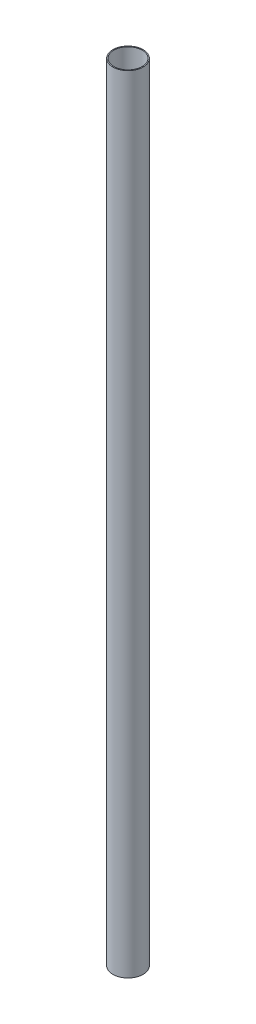
SolidWorks part; units mm, degrees
ref_plane "Front Plane" through (0, 0, 0) normal (0, 0, 1) x (1, 0, 0)
ref_plane "Top Plane" through (0, 0, 0) normal (0, 1, 0) x (1, 0, 0)
ref_plane "Right Plane" through (0, 0, 0) normal (1, 0, 0) x (0, 0, -1)
sketch "Sketch1" plane through (0, 0, 0) normal (0, 1, 0) x (1, 0, 0)
  circle A0 centre (0, 0) radius 31.75
  circle A1 centre (0, 0) radius 29.75
  dimension "D1" = 63.5
  dimension "D2" = 2
extrude "Boss-Extrude1" add sketch "Sketch1" along normal blind 1650
